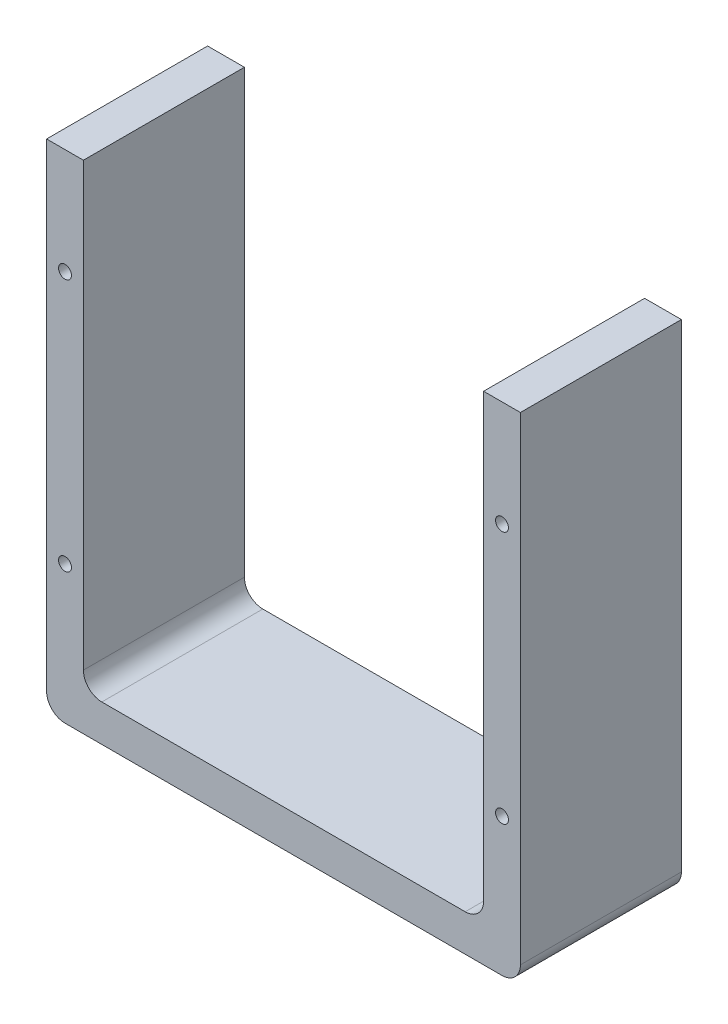
SolidWorks part; units mm, degrees
material "ABS"
ref_plane "前视基准面" through (0, 0, 0) normal (0, 0, 1) x (1, 0, 0)
ref_plane "上视基准面" through (0, 0, 0) normal (0, 1, 0) x (1, 0, 0)
ref_plane "右视基准面" through (0, 0, 0) normal (1, 0, 0) x (0, 0, -1)
sketch "草图1" plane through (0, 0, 0) normal (0, 0, 1) x (1, 0, 0)
  line L0 (0, 0) -> (0, 93.9248) construction
  line L1 (-43.5, 0) -> (43.5, 0)
  line L2 (43.5, 0) -> (43.5, 100)
  line L4 (-51.5, -8) -> (51.5, -8)
  line L5 (51.5, -8) -> (51.5, 100)
  line L6 (51.5, 100) -> (43.5, 100)
  line L7 (-51.5, 100) -> (-43.5, 100)
  line L8 (-51.5, -8) -> (-51.5, 100)
  line L9 (-43.5, 0) -> (-43.5, 100)
  dimension "D1" = 100
  dimension "D2" = 8
  dimension "D3" = 103
  dimension "D4" = 8
extrude "凸台-拉伸1" add sketch "草图1" along normal blind 35
sketch "草图2" plane through (0, 0, 35) normal (0, 0, 1) x (1, 0, 0)
  line L1 (-43.5, 0) -> (-43.5, 100) construction
  line L2 (-51.5, -8) -> (51.5, -8) construction
  line L3 (0, 0) -> (0, 36.5658) construction
  circle A0 centre (-47.5, 77) radius 1.25
  circle A1 centre (-47.5, 22) radius 1.25
  circle A2 centre (47.5, 22) radius 1.25
  circle A3 centre (47.5, 77) radius 1.25
  dimension "D3" = 2.5
  dimension "D4" = 2.5
  dimension "D6" = 4
  dimension "D1" = 55
  dimension "D2" = 4
  dimension "D5" = 30
hole_wizard "Ø2.8 (2.8) 直径孔1" positions "3D草图1" profile "草图3" hole size "Ø2.8" standard "GB" end condition through all
sketch3d "3D草图1"
  point P0 (-47.5, 77, 35)
  point P3 (-47.5, 22, 35)
  point P6 (47.5, 77, 35)
  point P9 (47.5, 22, 35)
sketch "草图3" plane through (-47.5, 77, 35) normal (1, 0, 0) x (0, -1, 0)
  line L0 (0, 0) -> (0, 35)
  line L1 (0, 35) -> (1.4, 35)
  line L2 (1.4, 35) -> (1.4, 0)
  line L5 (1.4, 0) -> (0, 0)
  line L11 (0, -6.35) -> (0, 107.95) construction
  dimension "通孔孔直径" = 2.8
  dimension "通孔孔深度" = 35
sketch "草图4" plane through (0, -8, 0) normal (0, -1, 0) x (1, 0, 0)
  line L0 (0, 35) -> (0, 0)
  line L1 (-51.5, 35) -> (51.5, 35) construction
  line L2 (-51.5, 9) -> (51.5, 9)
  line L3 (-51.5, 17.5) -> (51.5, 17.5)
  line L4 (-51.5, 35) -> (-51.5, 0) construction
  line L5 (51.5, 35) -> (51.5, 0) construction
  point P8 (0, 17.5)
  dimension "D1" = 26
sketch "草图9" plane through (0, -8, 0) normal (0, -1, 0) x (-1, 0, 0)
  text T0 "宁波大学" font "华文行楷" height in points 72
extrude "切除-拉伸3" cut sketch "草图9" against normal blind 2
fillet "圆角1" radius 4 4 edges at (51.5, -8, 17.5) (-51.5, -8, 17.5) (43.5, 0, 17.5) (-43.5, 0, 17.5)
